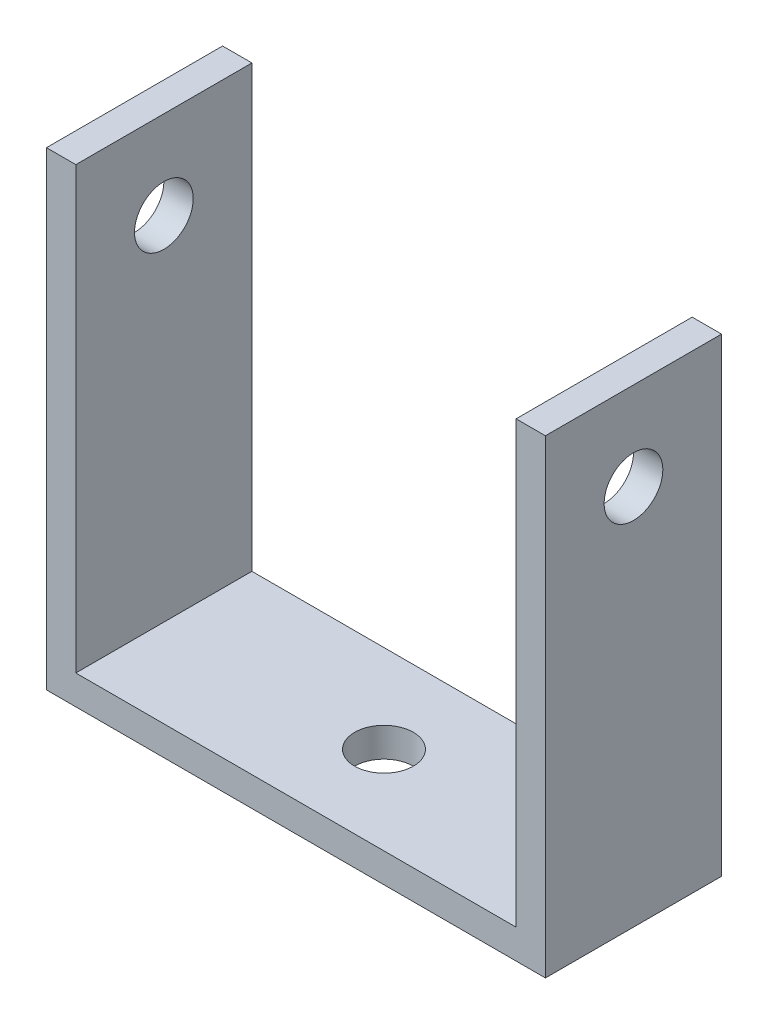
SolidWorks part; units mm, degrees
ref_plane "Front Plane" through (0, 0, 0) normal (0, 0, 1) x (1, 0, 0)
ref_plane "Top Plane" through (0, 0, 0) normal (0, 1, 0) x (1, 0, 0)
ref_plane "Right Plane" through (0, 0, 0) normal (1, 0, 0) x (0, 0, -1)
sketch "Sketch1" plane through (0, 0, 0) normal (0, 0, 1) x (1, 0, 0)
  line L0 (0, 0) -> (75, 0)
  line L1 (0, 0) -> (-75, 0)
  line L2 (-75, 0) -> (-75, 150)
  line L3 (75, 0) -> (75, 150)
  line L4 (-85, -10) -> (-85, 150)
  line L5 (0, -10) -> (-85, -10)
  line L6 (0, -10) -> (85, -10)
  line L7 (85, -10) -> (85, 150)
  line L8 (-85, 150) -> (-75, 150)
  line L9 (75, 150) -> (85, 150)
  point P11 (0, 0)
  dimension "D1" = 10
extrude "Boss-Extrude1" add sketch "Sketch1" along normal mid plane 60
sketch "Sketch2" plane through (85, 0, 0) normal (1, 0, 0) x (0, 0, -1)
  line L0 (-30, 150) -> (30, 150) construction
  line L1 (-30, -10) -> (-30, 150) construction
  circle A0 centre (0, 120) radius 10
  point P4 (0, 150)
  point P5 (0, 0)
  dimension "D1" = 30
  dimension "D2" = 30
extrude "Cut-Extrude1" cut sketch "Sketch2" against normal through all both and the other way through all
sketch "Sketch3" plane through (0, -10, 0) normal (0, -1, 0) x (1, 0, 0)
  circle A0 centre (0, 0) radius 10
extrude "Cut-Extrude2" cut sketch "Sketch3" against normal through all and the other way through all
